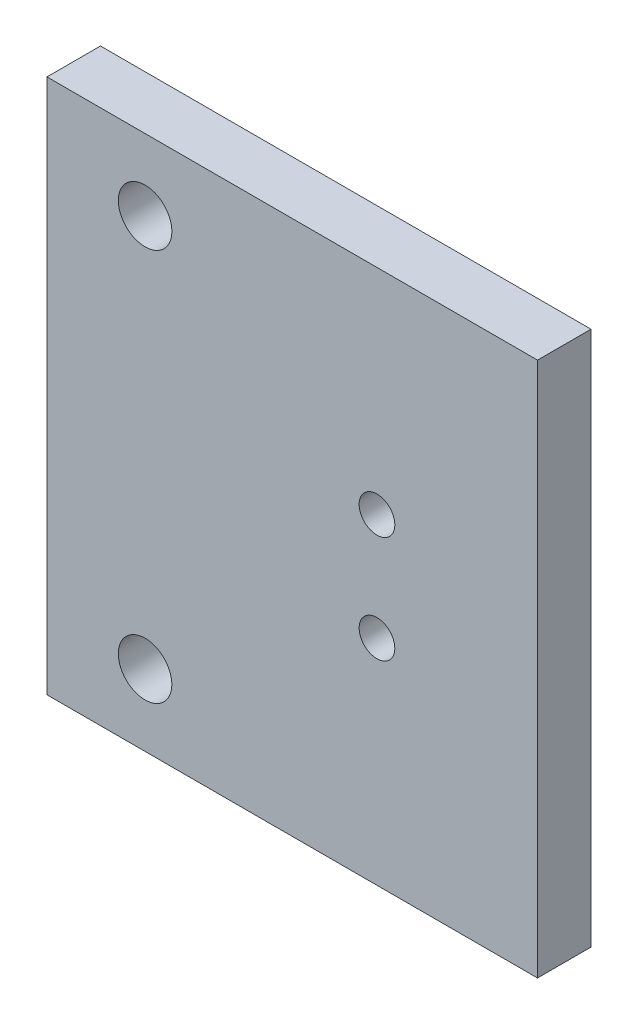
SolidWorks part; units mm, degrees
ref_plane "Alzado" through (0, 0, 0) normal (0, 0, 1) x (1, 0, 0)
ref_plane "Planta" through (0, 0, 0) normal (0, 1, 0) x (1, 0, 0)
ref_plane "Vista lateral" through (0, 0, 0) normal (1, 0, 0) x (0, 0, -1)
sketch "Croquis1" plane through (0, 0, 0) normal (0, 0, 1) x (1, 0, 0)
  line L0 (0, 15) -> (5.5, 15) construction
  line L5 (0, 0) -> (27.5, 0)
  line L6 (0, 0) -> (0, 30)
  line L7 (0, 30) -> (27.5, 30)
  line L8 (27.5, 0) -> (27.5, 30)
  line L9 (5.5, 15) -> (11, 15) construction
  line L10 (11, 15) -> (13.5, 15) construction
  line L11 (13.5, 15) -> (18.5, 15) construction
  line L12 (18.5, 15) -> (27.5, 15) construction
  line L13 (18.5, 18) -> (18.5, 12) construction
  line L14 (5.5, 26) -> (5.5, 4) construction
  circle A0 centre (18.5, 12) radius 1
  circle A1 centre (18.5, 18) radius 1
  circle A2 centre (5.5, 4) radius 1.5
  circle A3 centre (5.5, 26) radius 1.5
  dimension "D8" = 2
  dimension "D9" = 2
  dimension "D10" = 3
  dimension "D1" = 27.5
  dimension "D2" = 30
  dimension "D3" = 5.5
  dimension "D4" = 11
  dimension "D5" = 2.5
  dimension "D6" = 5
  dimension "D7" = 3
  dimension "D11" = 4
extrude "Saliente-Extruir1" add sketch "Croquis1" along normal blind 3
